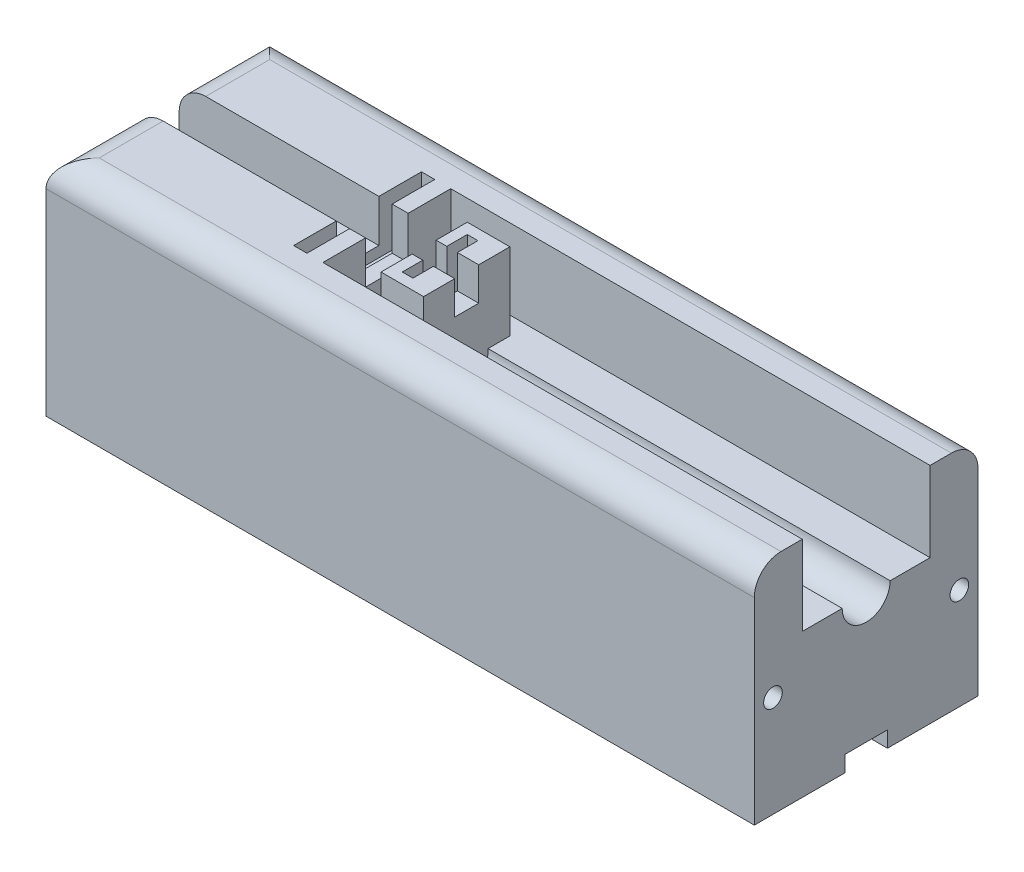
SolidWorks part; units mm, degrees
ref_plane "Front Plane" through (0, 0, 0) normal (0, 0, 1) x (1, 0, 0)
ref_plane "Top Plane" through (0, 0, 0) normal (0, 1, 0) x (1, 0, 0)
ref_plane "Right Plane" through (0, 0, 0) normal (1, 0, 0) x (0, 0, -1)
sketch "Sketch2" plane through (0, 0, 0) normal (1, 0, 0) x (0, 0, -1)
  line L0 (0, 0) -> (0, 15) construction
  line L1 (0, 0) -> (-21, 0) construction
  line L2 (0, 0) -> (21, 0) construction
  line L3 (-21, 0) -> (-21, 15)
  line L4 (-4, 15) -> (-21, 15)
  line L5 (21, 15) -> (21, 0)
  line L6 (0, 0) -> (21, 0)
  line L7 (0, 15) -> (0, 7) construction
  line L8 (0, 7) -> (4, 7) construction
  line L9 (0, 7) -> (-4, 7) construction
  line L10 (-4, 15) -> (-4, 7)
  line L11 (0, 7) -> (-4, 7)
  line L12 (4, 7) -> (4, 15)
  line L13 (4, 15) -> (21, 15)
  line L14 (0, 0) -> (-21, 0)
  line L15 (0, 7) -> (4, 7)
extrude "Boss-Extrude1" add sketch "Sketch2" along normal blind 8 and the other way blind 75
ref_plane "Plane1" through (0, 15, 0) normal (0, 1, 0) x (-1, 0, 0)
sketch "Sketch3" plane through (0, 15, 0) normal (0, 1, 0) x (-1, 0, 0)
  line L0 (-8, -12.5) -> (-5, -12.5) construction
  line L1 (-8, -21) -> (-8, -4) construction
  line L2 (-5, -12.5) -> (-2.5, -12.5) construction
  line L3 (75, -21) -> (-8, -21) construction
  line L4 (-5, -21) -> (-5, -12) construction
  line L5 (75, 21) -> (-8, 21) construction
  line L6 (-5, 21) -> (-5, 12) construction
  line L8 (-5, -12) -> (-2.5, -12)
  line L9 (-5, -12) -> (-5, 12)
  line L10 (-5, 12) -> (-2.5, 12)
  line L11 (-2.5, -12) -> (-2.5, 12)
extrude "Cut-Extrude1" cut sketch "Sketch3" against normal blind 10
ref_plane "Plane2" through (8, 0, 0) normal (1, 0, 0) x (0, 0, -1)
sketch "Sketch6" plane through (8, 0, 0) normal (1, 0, 0) x (0, 0, -1)
  line L0 (-12, 15) -> (-12, 0)
  line L1 (-21, 0) -> (21, 0) construction
  line L2 (-12, 0) -> (12, 0)
  line L3 (12, 0) -> (12, 15)
  line L4 (12, 15) -> (21, 15)
  line L5 (21, 15) -> (21, -27)
  line L6 (21, -27) -> (-21, -27)
  line L7 (-21, -27) -> (-21, 15)
  line L8 (-21, 15) -> (-12, 15)
extrude "Boss-Extrude6" add sketch "Sketch6" along normal blind 90 and the other way blind 83
sketch "Sketch7" plane through (8, 0, 0) normal (1, 0, 0) x (0, 0, -1)
  line L0 (2.25, 15) -> (2.25, 8.75)
  line L1 (2.25, 8.75) -> (-2.25, 8.75)
  line L2 (-5.1, 11) -> (-8.1, 11) construction
  line L3 (5.1, 11) -> (8.1, 11) construction
  line L4 (-5.1, 11) -> (5.1, 11) construction
  line L5 (-8.1, 11) -> (-8.1, 0)
  line L6 (12, 0) -> (-12, 0) construction
  line L7 (-8.1, 0) -> (8.1, 0)
  line L8 (8.1, 0) -> (8.1, 11)
  line L9 (8.1, 11) -> (8.1, 15)
  line L10 (12, 15) -> (4, 15) construction
  line L11 (8.1, 15) -> (2.25, 15)
  line L12 (0, 13.25) -> (2.25, 13.25) construction
  line L13 (2.25, 13.25) -> (2.25, 11) construction
  line L14 (2.25, 11) -> (2.25, 8.75) construction
  line L15 (2.25, 8.75) -> (0, 8.75) construction
  line L16 (0, 8.75) -> (-2.25, 8.75) construction
  line L17 (-2.25, 8.75) -> (-2.25, 11) construction
  line L18 (-2.25, 11) -> (-2.25, 13.25) construction
  line L19 (-2.25, 13.25) -> (0, 13.25) construction
  line L20 (-2.25, 8.75) -> (-2.25, 15)
  line L21 (-2.25, 15) -> (-8.1, 15)
  line L22 (-4, 15) -> (-12, 15) construction
  line L23 (-8.1, 15) -> (-8.1, 11)
  point P8 (0, 11)
extrude "Boss-Extrude7" add sketch "Sketch7" along normal blind 90
ref_plane "Plane4" through (0, 15, 0) normal (0, 1, 0) x (-1, 0, 0)
sketch "Sketch8" plane through (0, 15, 0) normal (0, 1, 0) x (-1, 0, 0)
  line L0 (-8, -8.1) -> (-15, -8.1)
  line L1 (-8, 23.1) -> (-8, -23.1) construction
  line L2 (-98, -8.1) -> (-8, -8.1) construction
  line L3 (-15, -8.1) -> (-15, 8.1)
  line L4 (-98, 8.1) -> (-8, 8.1) construction
  line L5 (-15, 8.1) -> (-8, 8.1)
  line L6 (-8, 8.1) -> (-8, -8.1)
extrude "Cut-Extrude2" cut sketch "Sketch8" against normal blind 15
sketch "Sketch9" plane through (0, 15, 0) normal (0, 1, 0) x (-1, 0, 0)
  line L1 (-15, 8.1) -> (-15, -8.1) construction
  line L2 (-15, 0) -> (-19, 0) construction
  line L7 (-17, -6.1) -> (-19, -6.1)
  line L8 (-19, -6.1) -> (-19, 6.1)
  line L9 (-19, 6.1) -> (-17, 6.1)
  line L10 (-17, 6.1) -> (-17, -6.1)
extrude "Cut-Extrude3" cut sketch "Sketch9" against normal blind 10
ref_plane "Plane5" through (98, 0, 0) normal (1, 0, 0) x (0, 0, -1)
sketch "Sketch11" plane through (98, 0, 0) normal (1, 0, 0) x (0, 0, -1)
  line L0 (-4, 7) -> (-4, 0) construction
  line L1 (-8.1, 0) -> (8.1, 0) construction
  line L2 (4, 7) -> (4, 0) construction
  line L3 (-4, 0) -> (4, 0) construction
  line L4 (0, 0) -> (0, -4) construction
  line L5 (4, 0) -> (4.5, 0) construction
  line L6 (-4, 0) -> (-4.5, 0) construction
  line L7 (4.5, 0) -> (8.1, 0)
  line L8 (8.1, 0) -> (8.1, 0.5)
  line L9 (8.1, 0) -> (8.1, 15) construction
  line L10 (8.1, 0.5) -> (4, 0.5)
  line L11 (4, 0.5) -> (4, 0)
  line L12 (-4.5, 0) -> (-8.1, 0)
  line L13 (-8.1, 0) -> (-8.1, 0.5)
  line L14 (-8.1, 15) -> (-8.1, 0) construction
  line L15 (-8.1, 0.5) -> (-4, 0.5)
  line L16 (-4, 0.5) -> (-4, 0)
  arc A0 (-4, 0) -> (4, 0) centre (0, 0) ccw
  arc A1 (4.5, 0) -> (-4.5, 0) centre (0, 0) cw
extrude "Cut-Extrude4" cut sketch "Sketch11" against normal blind 90
sketch "Sketch12" plane through (98, 0, 0) normal (1, 0, 0) x (0, 0, -1)
  line L0 (-2.25, 15) -> (-8.1, 15)
  line L1 (-8.1, 15) -> (-8.1, 0.5)
  line L2 (-8.1, 0.5) -> (-4, 0.5)
  line L3 (-4, 0.5) -> (-4, 0)
  line L4 (4, 0) -> (4, 0.5)
  line L5 (4, 0.5) -> (8.1, 0.5)
  line L6 (8.1, 0.5) -> (8.1, 15)
  line L7 (8.1, 15) -> (2.25, 15)
  line L8 (2.25, 15) -> (2.25, 8.75)
  line L9 (2.25, 8.75) -> (-2.25, 8.75)
  line L10 (-2.25, 8.75) -> (-2.25, 15)
  arc A0 (-4, 0) -> (4, 0) centre (0, 0) ccw
  arc A1 (-4, 0) -> (4, 0) centre (0, 0) ccw construction
extrude "Cut-Extrude5" cut sketch "Sketch12" against normal blind 75
sketch "Sketch13" plane through (8, 0, 0) normal (1, 0, 0) x (0, 0, -1)
  line L0 (-4, 0.5) -> (4, 0.5) construction
  circle A0 centre (0, 0) radius 1.75
  point P4 (0, 0.5)
extrude "Cut-Extrude6" cut sketch "Sketch13" against normal blind 83 and the other way blind 90
sketch "Sketch14" plane through (8, 0, 0) normal (1, 0, 0) x (0, 0, -1)
  circle A0 centre (0, 0) radius 2
extrude "Cut-Extrude7" cut sketch "Sketch14" against normal blind 83
sketch "Sketch16" plane through (98, 0, 0) normal (1, 0, 0) x (0, 0, -1)
  line L0 (0, 0) -> (0, -8) construction
  line L1 (0, -8) -> (17.5, -8) construction
  line L2 (0, -8) -> (-17.5, -8) construction
  circle A0 centre (17.5, -8) radius 1.75
  circle A1 centre (-17.5, -8) radius 1.75
extrude "Cut-Extrude8" cut sketch "Sketch16" against normal blind 3
ref_plane "Plane6" through (95, 0, 0) normal (1, 0, 0) x (0, 0, -1)
sketch "Sketch17" plane through (95, 0, 0) normal (1, 0, 0) x (0, 0, -1)
  line L0 (-21, -6) -> (-18, -6) construction
  line L1 (-21, 15) -> (-21, -27) construction
  line L2 (21, -6) -> (18, -6) construction
  line L3 (21, -27) -> (21, 15) construction
  line L4 (-4.5, 0) -> (-4.5, -27) construction
  line L5 (18, -6) -> (18, -27)
  line L6 (-21, -27) -> (21, -27) construction
  line L7 (18, -27) -> (-18, -27)
  line L8 (-18, -27) -> (-18, -6)
  line L9 (4.5, 0) -> (4.5, -27) construction
  line L10 (-18, -6) -> (-4.5, -6)
  line L11 (-4.5, -6) -> (-4.5, -9)
  line L12 (-4.5, -9) -> (4.5, -9)
  line L13 (4.5, -9) -> (4.5, -6)
  line L14 (4.5, -6) -> (18, -6)
extrude "Cut-Extrude9" cut sketch "Sketch17" against normal blind 170
sketch "Sketch18" plane through (95, 0, 0) normal (1, 0, 0) x (0, 0, -1)
  circle A1 centre (-17.5, -8) radius 2
  circle A2 centre (17.5, -8) radius 2
  point P5 (-17.5, -8)
  point P6 (17.5, -8)
extrude "Cut-Extrude10" cut sketch "Sketch18" against normal blind 15
sketch "Sketch19" plane through (95, 0, 0) normal (1, 0, 0) x (0, 0, -1)
  line L0 (0, 0) -> (0, -27) construction
  line L1 (-21, -27) -> (21, -27) construction
  line L2 (4, -27) -> (4, -24) construction
  line L3 (0, -27) -> (4, -27) construction
  line L4 (0, -27) -> (-4, -27) construction
  line L5 (-18, -27) -> (18, -27) construction
  line L6 (-4, -27) -> (-4, -24) construction
  line L7 (-4, -24) -> (4, -24) construction
  line L8 (-4, -27) -> (-4, -24)
  line L9 (-4, -24) -> (4, -24)
  line L10 (4, -24) -> (4, -27)
  line L11 (4, -27) -> (-4, -27)
extrude "Cut-Extrude11" cut sketch "Sketch19" along normal blind 3
sketch "Sketch20" plane through (8, 0, 0) normal (1, 0, 0) x (0, 0, -1)
  line L0 (-2, 0) -> (-2, -1) construction
  line L1 (-2, -1) -> (2, -1) construction
  line L2 (2, -1) -> (2, 0) construction
  line L3 (-2, -1) -> (-3.8783, -1) construction
  line L4 (2, -1) -> (3.8627, -1) construction
  line L5 (-3.8783, -1) -> (3.8783, -1)
  arc A0 (2, 0) -> (-2, 0) centre (0, 0) ccw construction
  circle A1 centre (0, 0) radius 2 construction
  arc A2 (-3.8783, -1) -> (3.8783, -1) centre (0, 0) ccw
extrude "Cut-Extrude12" cut sketch "Sketch20" along normal blind 7
sketch "Sketch21" plane through (0, 15, 0) normal (0, 1, 0) x (-1, 0, 0)
  line L0 (-15, -2.25) -> (-8, -2.25)
  line L1 (-8, 23.1) -> (-8, -23.1) construction
  line L2 (-15, 2.25) -> (-8, 2.25)
  line L3 (-8, 2.25) -> (-8, -2.25)
  line L4 (-15, -2.25) -> (-15, 2.25)
extrude "Cut-Extrude13" cut sketch "Sketch21" against normal blind 17
sketch "Sketch22" plane through (0, 15, 0) normal (0, 1, 0) x (-1, 0, 0)
  line L0 (75, -21) -> (35, -21)
  line L1 (75, -21) -> (-98, -21) construction
  line L2 (35, -21) -> (35, 21)
  line L3 (75, 21) -> (-98, 21) construction
  line L4 (35, 21) -> (75, 21)
  line L5 (75, 21) -> (75, -21)
extrude "Cut-Extrude14" cut sketch "Sketch22" against normal blind 42
fillet "Fillet1" radius 5 4 edges at (31.5, 15, -21) (-35, 15, -12.5) (-35, 15, 12.5) (31.5, 15, 21)
